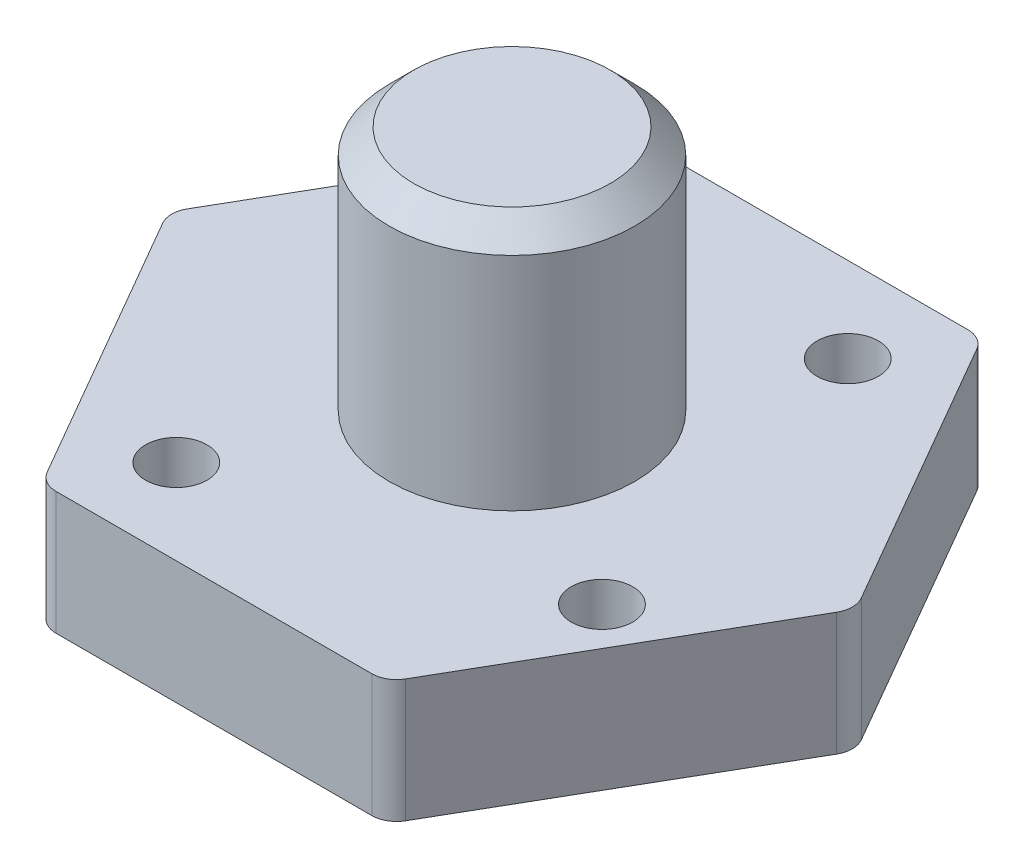
SolidWorks part; units mm, degrees
ref_plane "Спереди" through (0, 0, 0) normal (0, 0, 1) x (1, 0, 0)
ref_plane "Сверху" through (0, 0, 0) normal (0, 1, 0) x (1, 0, 0)
ref_plane "Справа" through (0, 0, 0) normal (1, 0, 0) x (0, 0, -1)
sketch "Эскиз1" plane through (0, 0, 0) normal (0, 1, 0) x (1, 0, 0)
  line L0 (0, 77.0654) -> (0, 0) construction
  line L1 (0, 0) -> (93.5211, 0) construction
  line L2 (0, 0) -> (7, 12.1244) construction
  line L3 (14, 0) -> (7, 12.1244)
  line L4 (7, 12.1244) -> (-7, 12.1244)
  line L5 (-7, 12.1244) -> (-14, 0)
  line L6 (-14, 0) -> (-7, -12.1244)
  line L7 (-7, -12.1244) -> (7, -12.1244)
  line L8 (7, -12.1244) -> (14, 0)
  circle A0 centre (0, 0) radius 14 construction
  circle A2 centre (5, 8.6603) radius 1.25
  circle A3 centre (8.6603, -5) radius 1.25
  circle A4 centre (-5, -8.6603) radius 1.25
  circle A5 centre (-8.6603, 5) radius 1.25
  point P21 (0, 0)
  dimension "D1" = 28
  dimension "D2" = 2.5
  dimension "D3" = 10
  dimension "D4" = 4
extrude "Бобышка-Вытянуть1" add sketch "Эскиз1" along normal blind 5
sketch "Эскиз2" plane through (0, 5, 0) normal (0, 1, 0) x (1, 0, 0)
  circle A0 centre (0, 0) radius 5
  dimension "D1" = 10
extrude "Бобышка-Вытянуть2" add sketch "Эскиз2" along normal blind 10
fillet "Скругление1" radius 1 6 edges at (-7, 2.5, -12.1244) (7, 2.5, -12.1244) (14, 2.5, 0) (7, 2.5, 12.1244) (-7, 2.5, 12.1244) (-14, 2.5, 0)
chamfer "Фаска1" distance 1 angle 45 1 edges at (0, 15, 5)
